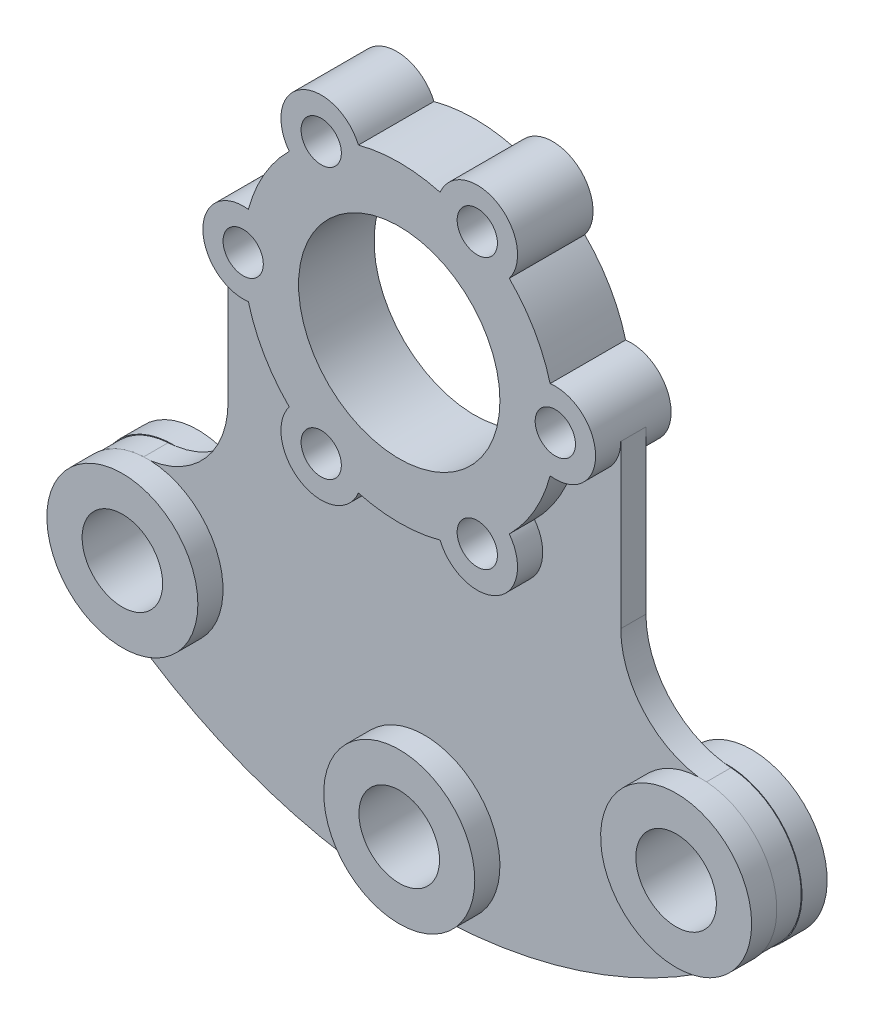
SolidWorks part; units mm, degrees
ref_plane "Front Plane" through (0, 0, 0) normal (0, 0, 1) x (1, 0, 0)
ref_plane "Top Plane" through (0, 0, 0) normal (0, 1, 0) x (1, 0, 0)
ref_plane "Right Plane" through (0, 0, 0) normal (1, 0, 0) x (0, 0, -1)
sketch "Sketch1" plane through (0, 0, 0) normal (0, 0, 1) x (1, 0, 0)
  circle A0 centre (0, 0) radius 20
  arc A1 (-21.8542, 21.9863) -> (-29.9677, 7.9331) centre (0, 0) ccw
  circle A2 centre (31, 0) radius 4
  circle A3 centre (15.5, -26.8468) radius 4
  circle A4 centre (-15.5, -26.8468) radius 4
  circle A5 centre (-31, 0) radius 4
  circle A6 centre (-15.5, 26.8468) radius 4
  circle A7 centre (15.5, 26.8468) radius 4
  arc A8 (29.9677, -7.9331) -> (29.9677, 7.9331) centre (31, 0) ccw
  arc A9 (8.1136, -29.9194) -> (21.8542, -21.9863) centre (15.5, -26.8468) ccw
  arc A10 (-21.8542, -21.9863) -> (-8.1136, -29.9194) centre (-15.5, -26.8468) ccw
  arc A11 (-29.9677, 7.9331) -> (-29.9677, -7.9331) centre (-31, 0) ccw
  arc A12 (-8.1136, 29.9194) -> (-21.8542, 21.9863) centre (-15.5, 26.8468) ccw
  arc A13 (21.8542, 21.9863) -> (8.1136, 29.9194) centre (15.5, 26.8468) ccw
  arc A14 (8.1136, 29.9194) -> (-8.1136, 29.9194) centre (0, 0) ccw
  arc A15 (29.9677, 7.9331) -> (21.8542, 21.9863) centre (0, 0) ccw
  arc A16 (21.8542, -21.9863) -> (29.9677, -7.9331) centre (0, 0) ccw
  arc A17 (-8.1136, -29.9194) -> (8.1136, -29.9194) centre (0, 0) ccw
  arc A18 (-29.9677, -7.9331) -> (-21.8542, -21.9863) centre (0, 0) ccw
  point P18 (0, 0)
  point P30 (0, 0)
  dimension "D1" = 62
  dimension "D2" = 40
  dimension "D3" = 6
  dimension "D4" = 6
extrude "Boss-Extrude1" add sketch "Sketch1" against normal blind 15
ref_plane "Plane1" through (0, 0, -7.5) normal (0, 0, 1) x (1, 0, 0)
sketch "Sketch3" plane through (0, 0, -7.5) normal (0, 0, 1) x (1, 0, 0)
  line L0 (0, 31) -> (0, -101.257) construction
  line L1 (-77.7825, 0) -> (94.8229, 0) construction
  line L2 (-77.7825, -65) -> (94.8229, -65) construction
  line L3 (39, 0) -> (39, -33.3366)
  line L4 (-39, 0) -> (-39, -32.2079)
  arc A0 (8.1136, 29.9194) -> (-8.1136, 29.9194) centre (0, 0) ccw construction
  circle A1 centre (55, -65) radius 14.8531
  circle A2 centre (55, -65) radius 8
  circle A3 centre (-55, -65) radius 14.8531
  circle A4 centre (-55, -65) radius 8
  arc A5 (-64.5942, -76.3386) -> (64.5942, -76.3386) centre (0, 0) ccw
  circle A8 centre (0, -85) radius 15
  circle A9 centre (0, -85) radius 8
  arc A10 (29.9677, -7.9331) -> (29.9677, 7.9331) centre (31, 0) ccw construction
  arc A11 (39, -32.2079) -> (55.9042, -50.1745) centre (57, -32.2079) ccw
  arc A12 (-39, -32.2079) -> (-55.9042, -50.1745) centre (-57, -32.2079) cw
  arc A13 (-29.9677, 7.9331) -> (-29.9677, -7.9331) centre (-31, 0) ccw construction
  arc A14 (-39, 0) -> (-29.9677, -7.9331) centre (-31, 0) ccw
  arc A15 (39, 0) -> (29.9677, -7.9331) centre (31, 0) cw
  circle A16 centre (0, 0) radius 31
  arc A17 (-21.8542, -21.9863) -> (-8.1136, -29.9194) centre (-15.5, -26.8468) ccw
  arc A18 (8.1136, -29.9194) -> (21.8542, -21.9863) centre (15.5, -26.8468) ccw
  point P52 (0, 0)
  dimension "D2" = 55
  dimension "D3" = 200
  dimension "D4" = 30
  dimension "D5" = 36
  dimension "D1" = 65
extrude "Boss-Extrude2" add sketch "Sketch3" along normal mid plane 5
sketch "Sketch4" plane through (0, 0, -5) normal (0, 0, 1) x (1, 0, 0)
  circle A0 centre (-55, -65) radius 15
  circle A1 centre (-55, -65) radius 8
  circle A2 centre (0, -85) radius 15
  circle A3 centre (0, -85) radius 8
  circle A4 centre (55, -65) radius 8
  circle A5 centre (55, -65) radius 15
extrude "Boss-Extrude3" add sketch "Sketch4" along normal blind 5
sketch "Sketch5" plane through (0, 0, -10) normal (0, 0, -1) x (-1, 0, 0)
  circle A0 centre (-55, -65) radius 8
  circle A1 centre (-55, -65) radius 15
  circle A2 centre (0, -85) radius 8
  circle A3 centre (0, -85) radius 15
  circle A4 centre (55, -65) radius 8
  circle A5 centre (55, -65) radius 15
extrude "Boss-Extrude4" add sketch "Sketch5" along normal blind 5
